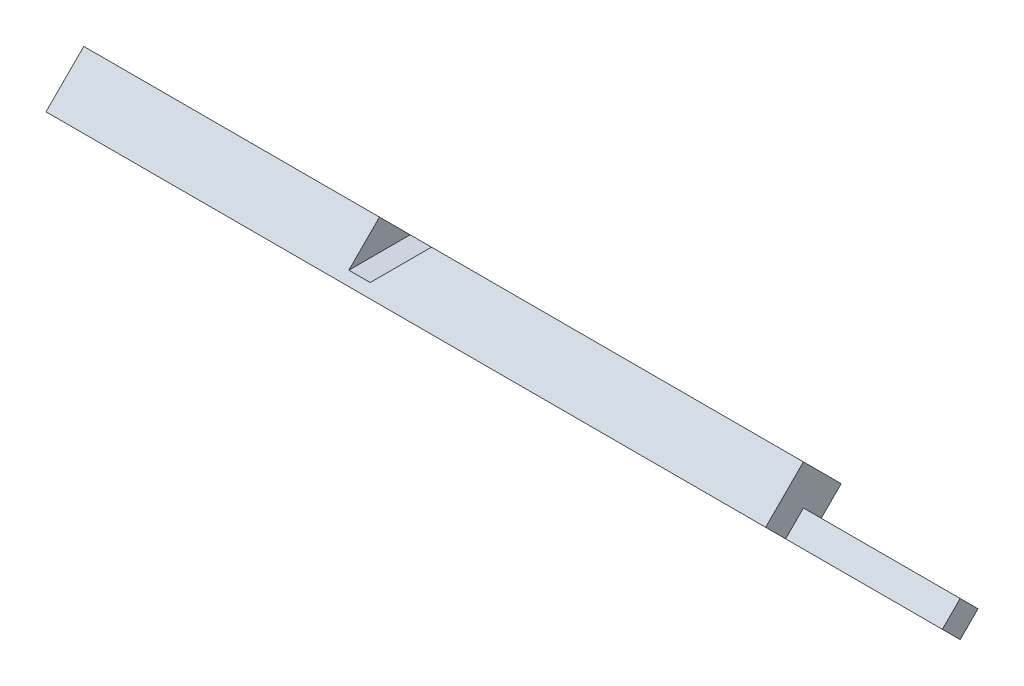
SolidWorks part; units mm, degrees
ref_plane "Front Plane" through (0, 0, 0) normal (0, 0, 1) x (1, 0, 0)
ref_plane "Top Plane" through (0, 0, 0) normal (0, 1, 0) x (1, 0, 0)
ref_plane "Right Plane" through (0, 0, 0) normal (1, 0, 0) x (0, 0, -1)
sketch "Sketch1" plane through (0, 0, 0) normal (1, 0, 0) x (0, 0, -1)
  line L0 (5.3033, 0) -> (0, 5.3033)
  line L1 (5.3033, 0) -> (0, -5.3033)
  line L2 (0, 5.3033) -> (-5.3033, 0)
  line L3 (0, -5.3033) -> (-5.3033, 0)
  line L4 (5.3033, 0) -> (-5.3033, 0) construction
  line L5 (0, 5.3033) -> (0, -5.3033) construction
  point P1 (0, 0)
  dimension "D1" = 7.5
extrude "Boss-Extrude1" add sketch "Sketch1" along normal blind 101
sketch "Sketch2" plane through (101, 0, 0) normal (1, 0, 0) x (0, 0, -1)
  line L9 (0, -5.3033) -> (-2.5, -2.8033)
  line L14 (0, -5.3033) -> (2.5, -2.8033)
  line L15 (-2.5, -2.8033) -> (0, -0.3033)
  line L16 (2.5, -2.8033) -> (0, -0.3033)
  line L17 (-5.3033, 0) -> (0, -5.3033) construction
  circle A0 centre (0, -2.8033) radius 2.5 construction
  dimension "D1" = 5
extrude "Boss-Extrude2" add sketch "Sketch2" along normal blind 22
sketch "Sketch3" plane through (0, 0, 0) normal (0, 1, 0) x (1, 0, 0)
  line L0 (101, 0) -> (0, 0) construction
  line L1 (44.5, 5.3033) -> (41.5, 5.3033)
  line L2 (44.5, 5.3033) -> (44.5, -5.3033)
  line L3 (44.5, -5.3033) -> (41.5, -5.3033)
  line L4 (41.5, 5.3033) -> (41.5, -5.3033)
  line L5 (44.5, 5.3033) -> (41.5, -5.3033) construction
  line L6 (44.5, -5.3033) -> (41.5, 5.3033) construction
  line L7 (101, -5.3033) -> (0, -5.3033) construction
  point P0 (43, 0)
  dimension "D1" = 43
  dimension "D2" = 3
extrude "Cut-Extrude1" cut sketch "Sketch3" along normal up to next from offset 1
sketch "Sketch4" plane through (0, 0, 0) normal (0, 0, 1) x (1, 0, 0)
  line L0 (44.5, 1) -> (48.8033, 5.3033)
  line L1 (101, 5.3033) -> (44.5, 5.3033) construction
  line L2 (48.8033, 5.3033) -> (44.5, 5.3033)
  line L3 (44.5, 5.3033) -> (44.5, 1)
  dimension "D1" = 45
extrude "Cut-Extrude2" cut sketch "Sketch4" against normal through all both and the other way through all
